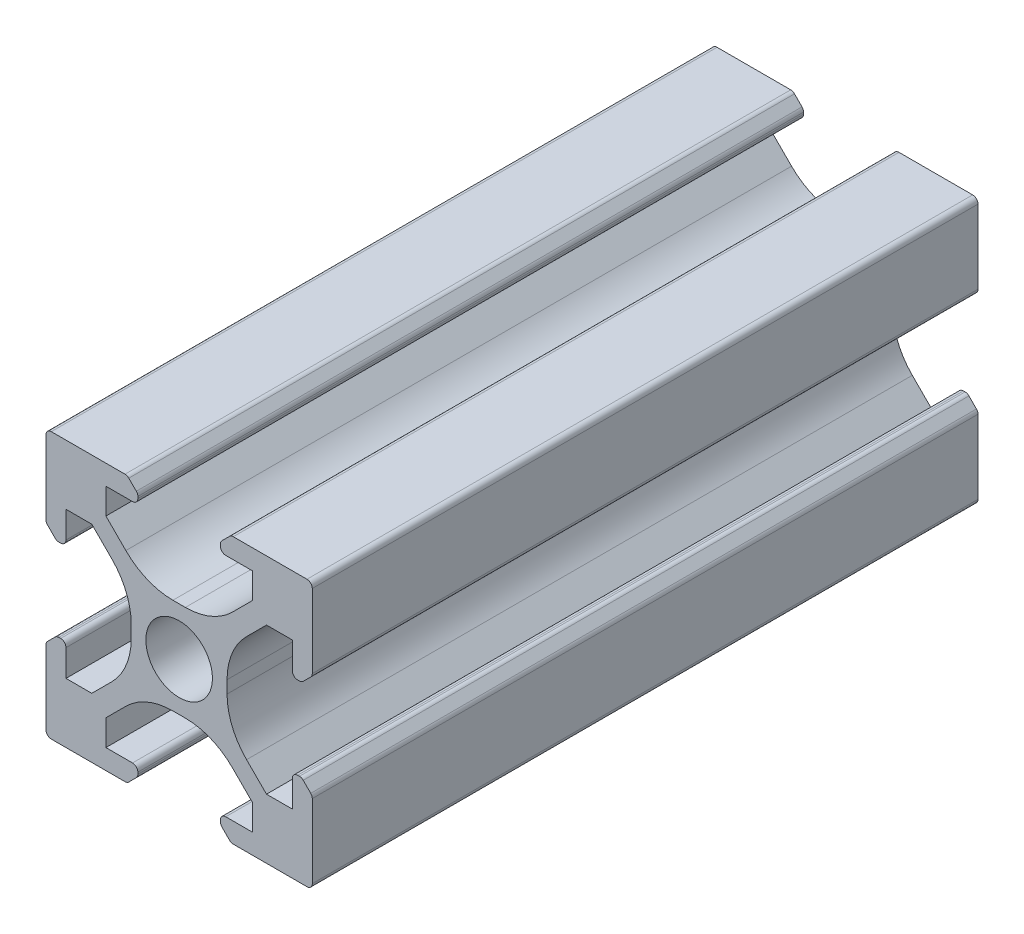
SolidWorks part; units mm, degrees
material "6063-T83"
ref_plane "Plano frontal" through (0, 0, 0) normal (0, 0, 1) x (1, 0, 0)
ref_plane "Plano superior" through (0, 0, 0) normal (0, 1, 0) x (1, 0, 0)
ref_plane "Plano direito" through (0, 0, 0) normal (1, 0, 0) x (0, 0, -1)
sketch "Esboço1" plane through (0, 0, 0) normal (0, 0, 1) x (1, 0, 0)
  line L0 (-9.0343, 3.1) -> (-8.9, 3.1)
  line L3 (-10, 10) -> (-4.0657, 10)
  line L5 (-10, -10) -> (10, 10) construction
  line L6 (-10, 10) -> (10, -10) construction
  line L7 (-8.5, 3.5) -> (-8.5, 5.5)
  line L8 (-10, 0) -> (10, 0) construction
  line L9 (0, 10) -> (0, -10) construction
  line L12 (-8.5, 5.5) -> (-6.5607, 5.5)
  line L15 (-6.5607, 5.5) -> (-5.0645, 4.0038)
  line L16 (-3.6, 0.4683) -> (-3.6, 0)
  line L17 (-0.4683, 3.6) -> (0, 3.6)
  line L18 (-5.5, 6.5607) -> (-4.0038, 5.0645)
  line L21 (-5.5, 8.5) -> (-5.5, 6.5607)
  line L24 (-3.5, 8.5) -> (-5.5, 8.5)
  line L25 (-3.1, 9.0343) -> (-3.1, 8.9)
  line L44 (-10, 4.0657) -> (-10, 10)
  line L45 (-9.8828, 3.7828) -> (-9.3172, 3.2172)
  line L46 (-3.7828, 9.8828) -> (-3.2172, 9.3172)
  line L47 (-3.6, 0) -> (-2.5, 0)
  line L48 (0, 3.6) -> (0, 2.5)
  arc A0 (-3.5, 8.5) -> (-3.1, 8.9) centre (-3.5, 8.9) ccw
  arc A1 (-3.7828, 9.8828) -> (-4.0657, 10) centre (-4.0657, 9.6) ccw
  arc A2 (-10, 4.0657) -> (-9.8828, 3.7828) centre (-9.6, 4.0657) ccw
  arc A3 (-8.5, 3.5) -> (-8.9, 3.1) centre (-8.9, 3.5) cw
  arc A4 (-3.2172, 9.3172) -> (-3.1, 9.0343) centre (-3.5, 9.0343) cw
  arc A5 (-9.3172, 3.2172) -> (-9.0343, 3.1) centre (-9.0343, 3.5) ccw
  arc A6 (-3.6, 0.4683) -> (-5.0645, 4.0038) centre (-8.6, 0.4683) ccw
  arc A7 (-4.0038, 5.0645) -> (-0.4683, 3.6) centre (-0.4683, 8.6) ccw
  circle A8 centre (0, 0) radius 2.5
  point P6 (-10, 3.1)
  point P28 (-3.1, 8.5)
  point P31 (-3.1, 10)
  point P33 (-3.9, 10)
  point P36 (-10, 3.9)
  point P39 (-8.5, 3.1)
  point P42 (-3.1, 9.2)
  point P45 (-9.2, 3.1)
  point P48 (-3.6, 2.5393)
  point P51 (-2.5393, 3.6)
  dimension "D5" = 10
  dimension "D9" = 0.4
  dimension "D10" = 0.4
  dimension "D11" = 5
  dimension "D12" = 5
  dimension "D13" = 5
  dimension "D1" = 6.9
  dimension "D2" = 1.5
  dimension "D3" = 3.6
  dimension "D4" = 1.5
  dimension "D6" = 2.4
  dimension "D7" = 3.6
  dimension "D8" = 45
extrude "Ressalto-extrusão1" add sketch "Esboço1" along normal blind 50
sketch "Esboço3" plane through (0, 0, 0) normal (1, 0, 0) x (0, 0, -1)
  line L0 (0, 0) -> (-50, 0) construction
  line L1 (-50, 2.5) -> (-50, 0) construction
  point P3 (-150.9107, 0)
pattern_circular "PadrãoCircular1" count 4 every 90 about axis through (0, 0, 0) along (0, 0, 1) of "Ressalto-extrusão1"
fillet "Filete1" radius 0.4 4 edges at (-10, -10, 25) (-10, 10, 25) (10, -10, 25) (10, 10, 25)
